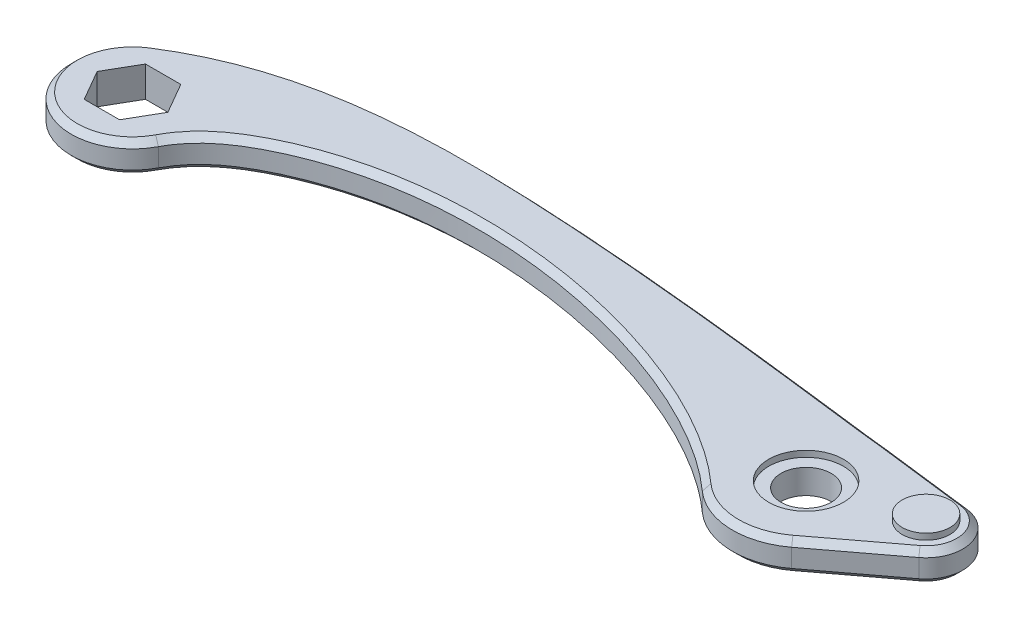
SolidWorks part; units mm, degrees
ref_plane "前视基准面" through (0, 0, 0) normal (0, 0, 1) x (1, 0, 0)
ref_plane "上视基准面" through (0, 0, 0) normal (0, 1, 0) x (1, 0, 0)
ref_plane "右视基准面" through (0, 0, 0) normal (1, 0, 0) x (0, 0, -1)
other "Configuration Table"
sketch "草图1" plane through (0, 0, 0) normal (0, 1, 0) x (1, 0, 0)
  line L0 (30.9096, 8.2822) -> (0, 0) construction
  line L1 (20.4085, 0) -> (-19.2141, 0) construction
  line L2 (32.3771, 20.1921) -> (2.935, 23.8199)
  line L3 (38.1355, -1.2984) -> (14.4517, -19.1611)
  arc A0 (2.935, 23.8199) -> (2.1116, 23.9069) centre (0, 0) ccw
  arc A1 (-230.7847, 16.8431) -> (-202.2854, -9.2841) centre (-220, 0) ccw
  arc A2 (38.1355, -1.2984) -> (32.3771, 20.1921) centre (30.9096, 8.2822) ccw
  arc A3 (24, 0) -> (23.1822, 6.2117) centre (0, 0) ccw
  arc A4 (0.8122, -23.9863) -> (14.4517, -19.1611) centre (0, 0) ccw
  arc A5 (-16.0471, -17.8463) -> (0.8122, -23.9863) centre (0, 0) ccw
  spline S0 degree 3 poles (2.1116, 23.9069) (-9.8109, 24.96) (-117.5794, 40.5525) (-200.5017, 36.2335) (-230.7847, 16.8431) knots 0 0 0 0 0.545538 1 1 1 1
  spline S1 degree 3 poles (-16.0471, -17.8463) (-50.2253, 12.8861) (-142.2814, 36.7861) (-197.94, -0.9926) (-202.2854, -9.2841) knots 0 0 0 0 0.861615 1 1 1 1
  dimension "D2" = 48
  dimension "D3" = 24
  dimension "D6" = 20
  dimension "D1" = 15
  dimension "D4" = 32
  dimension "D5" = 220
  dimension "D7" = 120
extrude "凸台-拉伸1" add sketch "草图1" along normal blind 10
sketch "草图2" plane through (0, 10, 0) normal (0, 1, 0) x (1, 0, 0)
  circle A0 centre (0, 0) radius 8.2
  dimension "D1" = 16.4
extrude "切除-拉伸1" cut sketch "草图2" against normal up to surface (10 mm away) up to face at (-19.9388, 0, -1.7965)
sketch "草图3" plane through (0, 10, 0) normal (0, 1, 0) x (1, 0, 0)
  arc A0 (38.1355, -1.2984) -> (32.3771, 20.1921) centre (30.9096, 8.2822) ccw construction
  arc A1 (38.1355, -1.2984) -> (32.3771, 20.1921) centre (30.9096, 8.2822) ccw construction
  circle A2 centre (30.9096, 8.2822) radius 7.8
  dimension "D1" = 15.6
extrude "凸台-拉伸2" add sketch "草图3" along normal blind 2
sketch "草图4" plane through (0, 12, 0) normal (0, 1, 0) x (1, 0, 0)
  circle A1 centre (30.9096, 8.2822) radius 7.8
  circle A2 centre (30.9096, 8.2822) radius 7.8 construction
  point P1 (30.9096, 8.2822)
  dimension "D1" = 0
sketch "草图6" plane through (0, 10, 0) normal (0, 1, 0) x (1, 0, 0)
  line L1 (-208.453, 0) -> (-214.2265, 10)
  line L2 (-214.2265, 10) -> (-225.7735, 10)
  line L3 (-225.7735, 10) -> (-231.547, 0)
  line L4 (-231.547, 0) -> (-225.7735, -10)
  line L5 (-225.7735, -10) -> (-214.2265, -10)
  line L6 (-214.2265, -10) -> (-208.453, 0)
  arc A0 (-230.7847, 16.8431) -> (-202.2854, -9.2841) centre (-220, 0) ccw construction
  arc A1 (-230.7847, 16.8431) -> (-202.2854, -9.2841) centre (-220, 0) ccw construction
  circle A2 centre (-220, 0) radius 10 construction
  dimension "D1" = 20
extrude "切除-拉伸2" cut sketch "草图6" against normal through all
chamfer "倒角1" distance 2 angle 45 16 edges at (2.5236, 0, -23.8669) (-233.5153, 0, 14.7424) (17.656, 0, -22.006) (42.5007, 0, -11.388) (-1.0337, 0, 23.9777) (26.2936, 0, 10.2297) (2.5236, 10, -23.8669) (-233.5153, 10, 14.7424) (17.656, 10, -22.006) (42.5007, 10, -11.388) (-1.0337, 10, 23.9777) (26.2936, 10, 10.2297)
sketch "草图12" plane through (0, 10, 0) normal (0, 1, 0) x (1, 0, 0)
  circle A0 centre (0, 0) radius 8.2 construction
  circle A1 centre (0, 0) radius 8.2 construction
  circle A2 centre (0, 0) radius 12.2
  dimension "D1" = 24.4
extrude "切除-拉伸3" cut sketch "草图12" against normal blind 2
